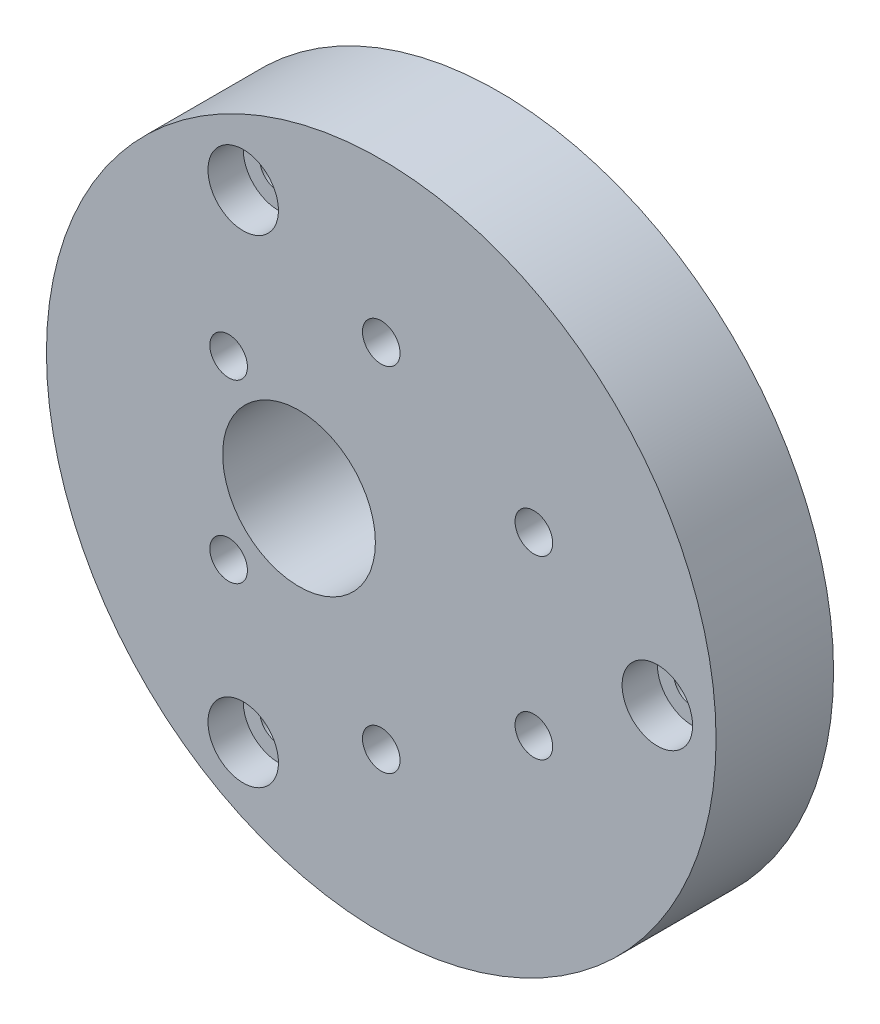
SolidWorks part; units mm, degrees
ref_plane "Alzado" through (0, 0, 0) normal (0, 0, 1) x (1, 0, 0)
ref_plane "Planta" through (0, 0, 0) normal (0, 1, 0) x (1, 0, 0)
ref_plane "Vista lateral" through (0, 0, 0) normal (1, 0, 0) x (0, 0, -1)
sketch "Croquis1" plane through (0, 0, 0) normal (0, 0, 1) x (1, 0, 0)
  line L0 (0, 0) -> (28.5, 0) construction
  line L1 (0, 0) -> (-7, 0) construction
  circle A0 centre (0, 0) radius 18.5
  circle A1 centre (0, 0) radius 28.5
  circle A2 centre (0, 0) radius 15 construction
  circle A3 centre (15, 0) radius 2.5
  circle A4 centre (0, 0) radius 23.5 construction
  circle A5 centre (23.5, 0) radius 2.5
  circle A6 centre (-7, 0) radius 6.5
  dimension "D1" = 37
  dimension "D3" = 30
  dimension "D4" = 5
  dimension "D6" = 5
  dimension "D8" = 13
  dimension "D7" = 7
  dimension "D2" = 10
  dimension "D5" = 5
extrude "Saliente-Extruir1" add sketch "Croquis1" along normal blind 10 contours A1 A5 A0 | A0 A3 | A5 | A3
sketch "Croquis2" plane through (0, 0, 10) normal (0, 0, 1) x (1, 0, 0)
  line L0 (0, 0) -> (28.5, 0) construction
  circle A0 centre (0, 0) radius 15 construction
  circle A1 centre (0, 0) radius 18.5 construction
  circle A2 centre (0, 0) radius 23.5 construction
  circle A3 centre (0, 0) radius 28.5 construction
  circle A4 centre (15, 0) radius 2.5
  circle A5 centre (23.5, 0) radius 2.5
  point P12 (23.5, 0)
  dimension "D1" = 30
  dimension "D2" = 37
  dimension "D4" = 5
  dimension "D5" = 5
  dimension "D3" = 5
hole_wizard "Refrentado para tornillo con cabeza troncocónica de M31" positions "Croquis2" profile "Croquis4" counterbore size "M3" standard "Ansi Metric"
sketch "Croquis4" plane through (23.5, 0, 10) normal (1, 0, 0) x (0, -1, 0)
  line L0 (0, 0) -> (0, 20.9614)
  line L1 (0, 20.9614) -> (1.6, 20)
  line L2 (1.6, 20) -> (1.6, 3)
  line L3 (1.6, 3) -> (3, 3)
  line L4 (3, 3) -> (3, 0)
  line L5 (3, 0) -> (0, 0)
  line L10 (0, 20.9614) -> (-1.6, 20) construction
  line L11 (0, -6.35) -> (0, 107.95) construction
  dimension "Diámetro de taladro" = 3.2
  dimension "Profundidad de taladro" = 20
  dimension "Diámetro de refrentado" = 6
  dimension "Profundidad de refrentado" = 3
  dimension "Ángulo de perforador" = 118
pattern_circular "MatrizC2" count 3 over 360 about axis through (0, 0, 0) along (0, 0, 1) of "Refrentado para tornillo con cabeza troncocónica de M31"
sketch "Croquis8" plane through (0, 0, 0) normal (0, 0, -1) x (-1, 0, 0)
  line L0 (0, 0) -> (-15, 0) construction
  line L1 (0, 0) -> (-12.9904, 7.5) construction
  circle A0 centre (0, 0) radius 15 construction
  circle A1 centre (-12.9904, 7.5) radius 2.5
  point P5 (-12.9904, 7.5)
  dimension "D1" = 30
  dimension "D3" = 5
  dimension "D2" = 30
hole_wizard "Refrentado para tornillo con cabeza troncocónica de M32" positions "Croquis8" profile "Croquis9" counterbore size "M3" standard "Ansi Metric"
sketch "Croquis9" plane through (12.9904, 7.5, 0) normal (1, 0, 0) x (0, 1, 0)
  line L0 (0, 0) -> (0, 20.9614)
  line L1 (0, 20.9614) -> (1.6, 20)
  line L2 (1.6, 20) -> (1.6, 3)
  line L3 (1.6, 3) -> (3, 3)
  line L4 (3, 3) -> (3, 0)
  line L5 (3, 0) -> (0, 0)
  line L10 (0, 20.9614) -> (-1.6, 20) construction
  line L11 (0, -6.35) -> (0, 107.95) construction
  dimension "Diámetro de taladro" = 3.2
  dimension "Profundidad de taladro" = 20
  dimension "Diámetro de refrentado" = 6
  dimension "Profundidad de refrentado" = 3
  dimension "Ángulo de perforador" = 118
pattern_circular "MatrizC3" count 6 over 360 about axis through (0, 0, 0) along (0, 0, 1) of "Refrentado para tornillo con cabeza troncocónica de M32"
